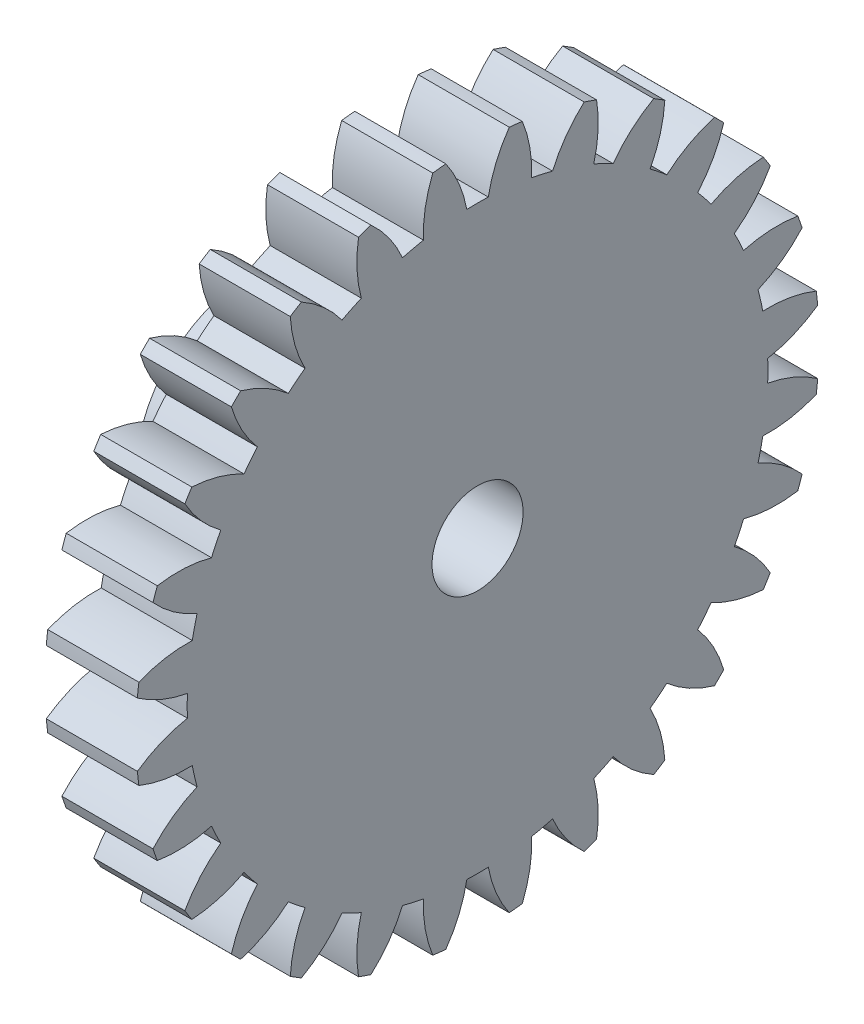
SolidWorks part; units mm, degrees
ref_plane "Plane1" through (0, 0, 0) normal (0, 0, 1) x (1, 0, 0)
ref_plane "Plane2" through (0, 0, 0) normal (0, 1, 0) x (1, 0, 0)
ref_plane "Plane3" through (0, 0, 0) normal (1, 0, 0) x (0, 0, -1)
sketch "HoldingSke" plane through (0, 0, 0) normal (0, 1, 0) x (1, 0, 0)
  line L0 (0, 0) -> (1.7659, -0.9389)
  line L1 (-15, 0) -> (100, 0) construction
  line L2 (0, 0) -> (-2.1039, 2.3779)
  line L3 (0, 0) -> (-11.863, 4.5341)
  line L4 (0, 0) -> (7.6251, 4.0544)
  line L5 (0, 0) -> (-4.6848, -1.7473)
  line L6 (0, 0) -> (-1.6579, -1.1186)
  line L7 (-2.1039, 2.3779) -> (-1.0276, 7.2607)
  line L8 (-76.2, 54.61) -> (-75.9, 54.61)
  line L9 (-71.009, 38.7566) -> (-53.1078, 45.2721)
  line L10 (-76.2, 71.12) -> (104.1128, 71.12)
  line L11 (0, 0) -> (-2, 0)
  line L12 (-76.2, 101.6) -> (-76.181, 101.6)
  line L13 (24.9733, 27.94) -> (52.9518, 28.4284)
  line L14 (24.9733, 27.94) -> (24.9743, 27.94)
  line L15 (24.9733, 27.94) -> (100.4006, 29.5858)
  line L16 (-63.627, -0.5) -> (-12.827, -0.5)
  circle A0 centre (0, 0) radius 1
  circle A1 centre (0, 0) radius 2.5
  circle A2 centre (0, 0) radius 2.5
  circle A3 centre (0, 0) radius 1
  dimension "MHD" = 5
  dimension "Hub_dia" = 5
  dimension "Bore" = 2
  dimension "MBD" = 2
  dimension "Num_teeth" = 28
  dimension "Pitch" = 2
  dimension "Overall_len" = 5
  dimension "Show_teeth" = 28
  dimension "Thickness" = 2
  dimension "OAL" = 5.0001
  dimension "T_dim" = 0.3
  dimension "Ap" = 20
  dimension "H" = 19.05
  dimension "Pitch_radius" = 180.3128
  dimension "Width" = 2
  dimension "Backlash" = 0.019
  dimension "Addendum_fac" = 1
  dimension "Dedendum_fac" = 1.25
  dimension "Clearance_fac" = 0.25
  dimension "Dedendum_add" = 0.001
  dimension "Module" = 0.5
sketch "BasProSke" plane through (0, 0, 0) normal (0, 1, 0) x (1, 0, 0)
  line L0 (-10, 0) -> (60, 0) construction
  line L1 (0, 0) -> (0, 7.5)
  line L2 (0, 0) -> (2, 0)
  line L3 (2, 0) -> (2, 7.5)
  line L4 (2, 7.5) -> (0, 7.5)
  dimension "Thickness" = 2
  dimension "Diameter" = 15
revolve "Base-Revolve" add sketch "BasProSke" angle 360 about L0
sketch "TooCutSke" plane through (0, 0, 0) normal (1, 0, 0) x (0, 0, -1)
  line L1 (0, 0) -> (0, 107) construction
  line L2 (0, 0) -> (-0.4257, 6.987) construction
  line L3 (0, 0) -> (-1.5654, 13.8936) construction
  line L4 (-0.4257, 6.987) -> (-0.7827, 6.9468) construction
  arc A0 (0.2356, 6.3696) -> (-0.2356, 6.3696) centre (0, 0) ccw
  arc A1 (0.7134, 7.4915) -> (-0.7134, 7.4915) centre (0, 0) ccw
  circle A2 centre (0, 0) radius 7 construction
  circle A3 centre (0, 0) radius 6.5778 construction
  arc A4 (-0.2356, 6.3696) -> (-0.7134, 7.4915) centre (-2.9887, 5.8597) ccw
  arc A5 (0.7134, 7.4915) -> (0.2356, 6.3696) centre (2.9887, 5.8597) ccw
  dimension "Root_dia" = 12.748
  dimension "Overcut_dia" = 15.0508
  dimension "Pitch_dia" = 14
  dimension "Base_dia" = 13.1557
  dimension "Flank_rad" = 2.8
  dimension "Half_ang" = 6.429
  dimension "Half_CT" = 0.3592
extrude "ToothCut" cut sketch "TooCutSke" along normal through all
fillet "Breaks" [suppressed] radius 0.01
fillet "RootFillets" [suppressed] radius 0.126
pattern_circular "TeethCuts" count 28 every 12.857 about axis through (-10, 0, 0) along (1, 0, 0) of "ToothCut", "RootFillets", "Breaks"
sketch "HubNeaOneSke" plane through (0, 0, 0) normal (-1, 0, 0) x (0, 0, 1)
  circle A0 centre (0, 0) radius 2.5
  dimension "Diameter" = 5
extrude "HubNearOne" add sketch "HubNeaOneSke" along normal blind 3.0001
sketch "HubNeaBotSke" plane through (0, 0, 0) normal (-1, 0, 0) x (0, 0, 1)
  circle A0 centre (0, 0) radius 2.5
  dimension "Diameter" = 5
extrude "HubNearBoth" [suppressed] add sketch "HubNeaBotSke" along normal blind 1.5
ref_plane "FarPln" through (2, 0, 0) normal (1, 0, 0) x (0, 0, -1)
sketch "HubFarSke" plane through (2, 0, 0) normal (1, 0, 0) x (0, 0, -1)
  circle A0 centre (0, 0) radius 2.5
  dimension "Diameter" = 5
extrude "HubFar" [suppressed] add sketch "HubFarSke" along normal blind 1.5
sketch "BorSke" plane through (0, 0, 0) normal (1, 0, 0) x (0, 0, -1)
  circle A0 centre (0, 0) radius 1
  dimension "Diameter" = 2
extrude "Bore" cut sketch "BorSke" along normal mid plane 10.0001
sketch "KeySke" plane through (0, 0, 0) normal (1, 0, 0) x (0, 0, -1)
  line L0 (-0.4, 0) -> (-0.4, 1.3)
  line L1 (-0.4, 1.3) -> (0.4, 1.3)
  line L2 (0.4, 1.3) -> (0.4, 0)
  line L3 (0, 0) -> (0, 34) construction
  line L4 (-0.4, 0) -> (0.4, 0)
  dimension "Offset" = 1.3
  dimension "Width" = 0.8
extrude "Keyway" [suppressed] cut sketch "KeySke" along normal mid plane 10.0001
pattern_circular "Keyway2" [suppressed] count 2 every 90 about axis through (-10, 0, 0) along (1, 0, 0)
equation "' \"Module@HoldingSke\" = 6.35"
equation "' \"Num_teeth@HoldingSke\" = 12"
equation "' \"Ap@HoldingSke\" =  20"
equation "' \"Ap@HoldingSke\" = 20"
equation "' \"Width@HoldingSke\" = 0.5 * 25.4"
equation "' \"Hub_dia@HoldingSke\"= 1 * 25.4"
equation "' \"Hub_dia@HoldingSke\" = 1 * 25.4"
equation "' \"Overall_len@HoldingSke\" = 1.0 * 25.4"
equation "' \"Bore@HoldingSke\" = 0.75 * 25.4"
equation "' \"T_dim@HoldingSke\" = 0.1 * 25.4"
equation "' \"Width@KeySke\" = 0.25 * 25.4"
equation "' \"Show_teeth@HoldingSke\" = 13"
equation "' \"Backlash@HoldingSke\" = 0.009 * 25.4"
equation "' \"Addendum_fac@HoldingSke\" = 1.0"
equation "' \"Dedendum_fac@HoldingSke\" = 1.25"
equation "' \"Dedendum_add@HoldingSke\" = 0.00005 * 25.4"
equation "' \"Clearance_fac@HoldingSke\" = 0.25"
equation "\"Pitch@HoldingSke\" = 1 / \"Module@HoldingSke\""
equation "\"Overcut_dia@TooCutSke\" = (\"Num_teeth@HoldingSke\" + 2 * \"Addendum_fac@HoldingSke\") / \"Pitch@HoldingSke\" + 0.002 * 25.4"
equation "\"Pitch_dia@TooCutSke\" = \"Num_teeth@HoldingSke\" / \"Pitch@HoldingSke\""
equation "\"Base_dia@TooCutSke\" = \"Num_teeth@HoldingSke\" / \"Pitch@HoldingSke\" * cos((\"Ap@HoldingSke\"  * 3.14159265 / 180))"
equation "\"Root_dia@TooCutSke\" = (\"Num_teeth@HoldingSke\" + 2) / \"Pitch@HoldingSke\" - 2 * (\"Addendum_fac@HoldingSke\" + \"Dedendum_fac@HoldingSke\") / \"Pitch@HoldingSke\" - \"Dedendum_add@HoldingSke\" * 2"
equation "\"Half_ang@TooCutSke\" = 180 / \"Num_teeth@HoldingSke\""
equation "\"Half_CT@TooCutSke\" = \"Num_teeth@HoldingSke\" / \"Pitch@HoldingSke\" * sin((3.14159265 / 2 / \"Num_teeth@HoldingSke\")) / 2 - 7 * \"Backlash@HoldingSke\" / 4"
equation "\"Flank_rad@TooCutSke\" = \"Num_teeth@HoldingSke\" / \"Pitch@HoldingSke\" / 5"
equation "\"Radius@RootFillets\" = \"Clearance_fac@HoldingSke\" / \"Pitch@HoldingSke\" + \"Dedendum_add@HoldingSke\""
equation "\"Break_rad@Breaks\" = 0.02 / \"Pitch@HoldingSke\""
equation "\"Thickness@HoldingSke\" = \"Width@HoldingSke\""
equation "\"OAL@HoldingSke\" = \"Thickness@HoldingSke\""
equation "\"MHD@HoldingSke\" = (\"Num_teeth@HoldingSke\" + 2) / \"Pitch@HoldingSke\" - 2 * (\"Addendum_fac@HoldingSke\" + \"Dedendum_fac@HoldingSke\")  / \"Pitch@HoldingSke\" - \"Dedendum_add@HoldingSke\" * 2"
equation "\"MBD@HoldingSke\" = (\"Num_teeth@HoldingSke\" + 2) / \"Pitch@HoldingSke\" - 2 * (\"Addendum_fac@HoldingSke\" + \"Dedendum_fac@HoldingSke\")  / \"Pitch@HoldingSke\" - \"Dedendum_add@HoldingSke\" * 2 - 0.002 * 25.4"
equation "\"MHD@HoldingSke\" = ((sgn( \"MHD@HoldingSke\" - \"Hub_dia@HoldingSke\" )-1)*( \"MHD@HoldingSke\" - \"Hub_dia@HoldingSke\" ))/-2+ \"Hub_dia@HoldingSke\""
equation "\"MBD@HoldingSke\" = ((sgn( \"MBD@HoldingSke\" - \"Bore@HoldingSke\" )-1)*( \"MBD@HoldingSke\" - \"Bore@HoldingSke\" ))/-2+ \"Bore@HoldingSke\""
equation "\"OAL@HoldingSke\" = ((sgn( \"OAL@HoldingSke\" - \"Overall_len@HoldingSke\" )+1)*( \"OAL@HoldingSke\" - \"Overall_len@HoldingSke\" ))/2 + \"Overall_len@HoldingSke\" + 0.000002 * 25.4"
equation "\"Num_teeth@TeethCuts\" = int( \"Show_teeth@HoldingSke\" ) + 1"
equation "\"Num_teeth@TeethCuts\" = ((sgn( \"Num_teeth@TeethCuts\" - \"Num_teeth@HoldingSke\" )-1)*( \"Num_teeth@TeethCuts\" - \"Num_teeth@HoldingSke\" ))/-2+ \"Num_teeth@HoldingSke\""
equation "\"Num_teeth@TeethCuts\" = ((sgn( \"Num_teeth@TeethCuts\" - 2.0)+1)*( \"Num_teeth@TeethCuts\" - 2.0))/2 +2.0"
equation "\"Angle@TeethCuts\" = 360.0 / \"Num_teeth@HoldingSke\""
equation "\"Diameter@BasProSke\" = (\"Num_teeth@HoldingSke\" + 2 * \"Addendum_fac@HoldingSke\") / \"Pitch@HoldingSke\""
equation "\"Thickness@BasProSke\"  = \"Thickness@HoldingSke\""
equation "' \"Fillet_rad@BasProSke\" =  \"Thickness@HoldingSke\" * 0.05"
equation "' \"Fillet_rad@BasProSke\" = \"Thickness@HoldingSke\" * 0.05"
equation "\"MHD@HoldingSke\" = ((sgn( \"MHD@HoldingSke\" - \"Root_dia@TooCutSke\" )-1)*( \"MHD@HoldingSke\" - \"Root_dia@TooCutSke\" ))/-2+ \"Root_dia@TooCutSke\""
equation "\"Diameter@HubNeaOneSke\" = \"MHD@HoldingSke\""
equation "\"Length@HubNearOne\" = \"OAL@HoldingSke\" - \"Thickness@BasProSke\""
equation "\"Diameter@HubNeaBotSke\" = \"MHD@HoldingSke\""
equation "\"Length@HubNearBoth\" = ( \"OAL@HoldingSke\" - \"Thickness@BasProSke\" ) / 2.0"
equation "\"Thickness@FarPln\" = \"Thickness@BasProSke\""
equation "\"Diameter@HubFarSke\" = \"MHD@HoldingSke\""
equation "\"Length@HubFar\" = ( \"OAL@HoldingSke\" - \"Thickness@BasProSke\" ) / 2.0"
equation "\"Diameter@BorSke\" = \"MBD@HoldingSke\""
equation "\"D1@Bore\" = \"OAL@HoldingSke\" * 2.0"
equation "\"D1@Keyway\" = \"OAL@HoldingSke\" * 2.0"
equation "\"Offset@KeySke\" = \"T_dim@HoldingSke\" + \"MBD@HoldingSke\" / 2.0"
